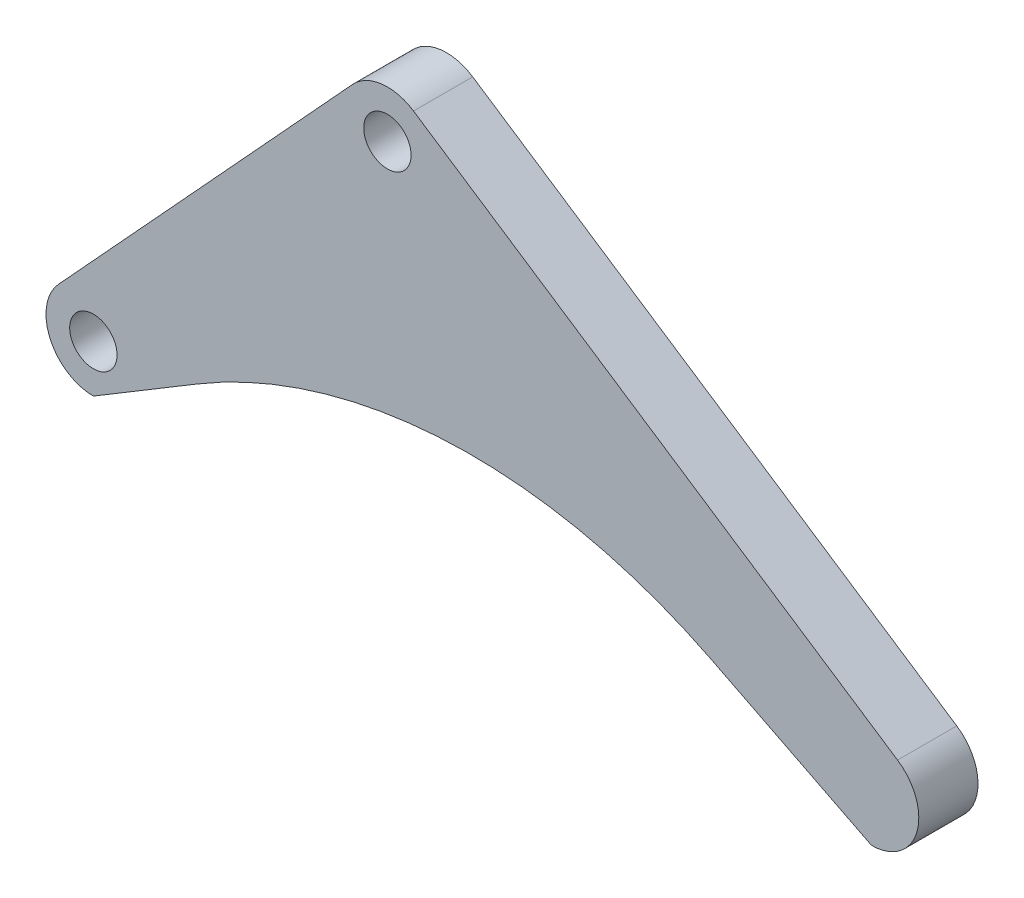
SolidWorks part; units mm, degrees
ref_plane "前基準面" through (0, 0, 0) normal (0, 0, 1) x (1, 0, 0)
ref_plane "上基準面" through (0, 0, 0) normal (0, 1, 0) x (1, 0, 0)
ref_plane "右基準面" through (0, 0, 0) normal (1, 0, 0) x (0, 0, -1)
sketch "草圖2" plane through (0, 0, 0) normal (0, 0, 1) x (1, 0, 0)
  line L0 (0, 0) -> (24.8279, 27.0272) construction
  line L1 (24.8279, 27.0272) -> (65.7, 0) construction
  line L2 (65.7, 0) -> (0, 0) construction
  line L3 (27.0342, 30.3637) -> (67.9063, 3.3365)
  line L4 (65.7, -4) -> (0, -4) construction
  line L5 (-2.9457, 2.706) -> (21.8821, 29.7332)
  line L6 (79.001, -4) -> (-9.1061, -4) construction
  line L7 (24.1894, 32.2448) -> (79.001, -4) construction
  line L8 (-9.1061, -4) -> (24.1894, 32.2448) construction
  line L9 (0, -4) -> (8.7003, 1.2308)
  line L10 (52.1757, 2.8312) -> (65.7, -4)
  circle A0 centre (0, 0) radius 2
  circle A1 centre (24.8279, 27.0272) radius 2
  arc A3 (65.7, -4) -> (67.9063, 3.3365) centre (65.7, 0) ccw
  arc A4 (0, -4) -> (-2.9457, 2.706) centre (0, 0) cw
  arc A5 (21.8821, 29.7332) -> (27.0342, 30.3637) centre (24.8279, 27.0272) cw
  arc A6 (52.1757, 2.8312) -> (8.7003, 1.2308) centre (31.8872, -37.3356) ccw
  point P21 (29.9961, 14.0342)
  dimension "D5" = 4
  dimension "D6" = 4
  dimension "D9" = 45
  dimension "D1" = 36.7
  dimension "D2" = 49
  dimension "D3" = 65.7
  dimension "D4" = 4
  dimension "D7" = 35
  dimension "D8" = 40
extrude "填料-伸長1" add sketch "草圖2" along normal mid plane 5
